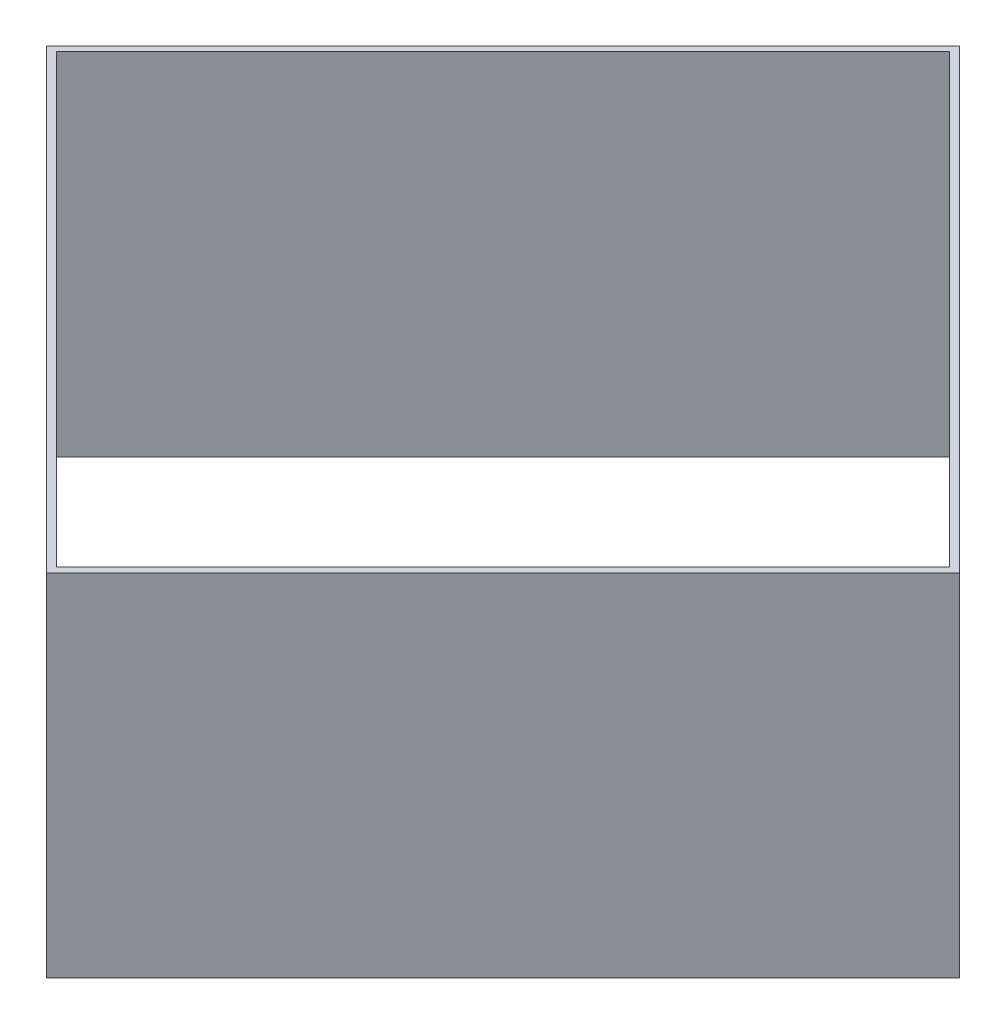
SolidWorks part; units mm, degrees
ref_plane "Спереди" through (0, 0, 0) normal (0, 0, 1) x (1, 0, 0)
ref_plane "Сверху" through (0, 0, 0) normal (0, 1, 0) x (1, 0, 0)
ref_plane "Справа" through (0, 0, 0) normal (1, 0, 0) x (0, 0, -1)
sketch "Эскиз1" plane through (0, 0, 0) normal (0, 1, 0) x (1, 0, 0)
  line L0 (0, -12.7279) -> (-12.7279, 0)
  line L5 (0, -12.7279) -> (12.7279, 0)
  line L6 (-12.7279, 0) -> (0, 12.7279)
  line L7 (12.7279, 0) -> (0, 12.7279)
  line L8 (-6.364, 6.364) -> (6.364, -6.364) construction
  line L9 (-6.364, -6.364) -> (6.364, 6.364) construction
  line L10 (0, 12.7279) -> (0, 0) construction
  point P1 (0, 0)
  dimension "D1" = 18
extrude "Вытянуть-Тонкостенный1" add sketch "Эскиз1" along normal blind 10 thin thin type one direction wall 0.2
